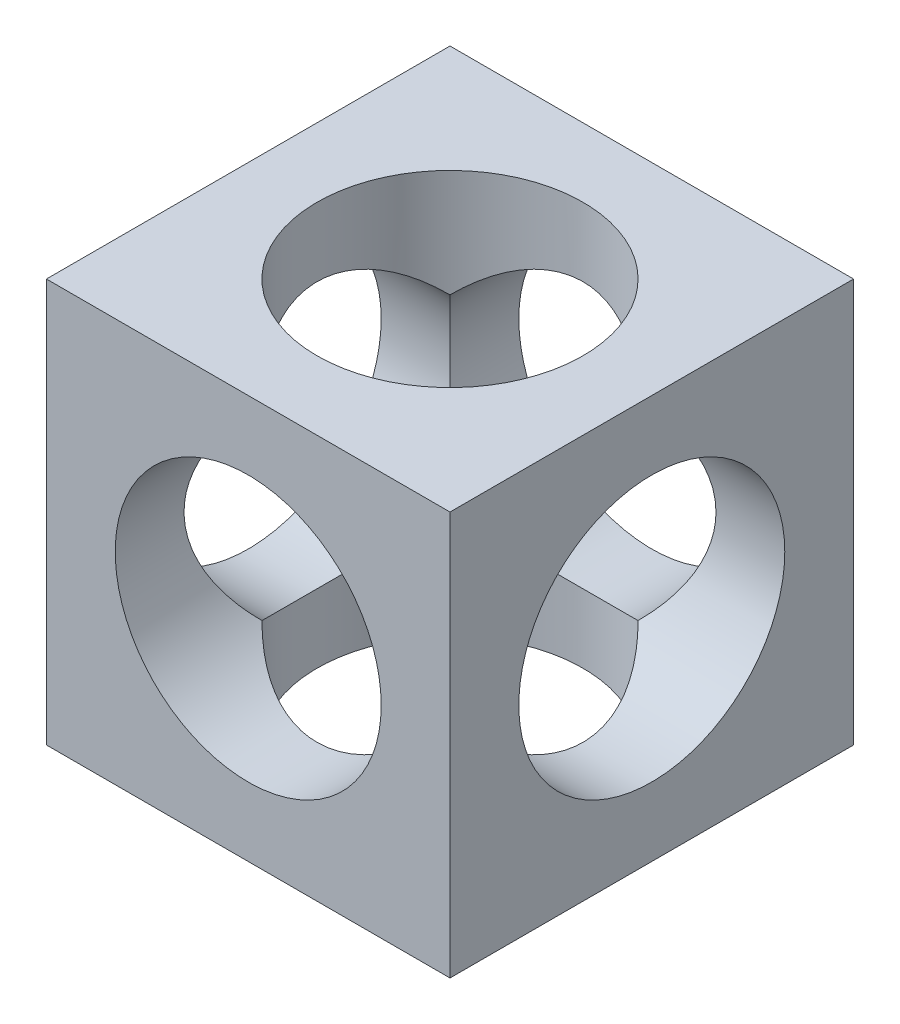
SolidWorks part; units mm, degrees
ref_plane "Front Plane" through (0, 0, 0) normal (0, 0, 1) x (1, 0, 0)
ref_plane "Top Plane" through (0, 0, 0) normal (0, 1, 0) x (1, 0, 0)
ref_plane "Right Plane" through (0, 0, 0) normal (1, 0, 0) x (0, 0, -1)
sketch "Esquisse1" plane through (0, 0, 0) normal (0, 0, 1) x (1, 0, 0)
  line L1 (-11, -11) -> (11, -11)
  line L2 (-11, -11) -> (-11, 11)
  line L3 (-11, 11) -> (11, 11)
  line L4 (11, -11) -> (11, 11)
  line L5 (-11, -11) -> (11, 11) construction
  line L6 (-11, 11) -> (11, -11) construction
  point P0 (0, 0)
  dimension "D1" = 22
extrude "Boss.-Extru.1" add sketch "Esquisse1" along normal blind 22
hole_wizard "Dégagement M131" positions "Esquisse3D1" profile "Esquisse2" hole size "M13" standard "ISO"
sketch3d "Esquisse3D1"
  line L0 (0, 11, 22) -> (0, 11, 0) construction
  line L1 (11, 11, 22) -> (-11, 11, 22) construction
  line L2 (11, 11, 0) -> (-11, 11, 0) construction
  line L4 (-11, 11, 11) -> (11, 11, 11) construction
  line L5 (-11, 11, 22) -> (-11, 11, 0) construction
  line L6 (11, 11, 22) -> (11, 11, 0) construction
  line L10 (11, 11, 11) -> (11, -11, 11) construction
  line L11 (11, -11, 22) -> (11, -11, 0) construction
  line L13 (0, 11, 22) -> (0, -11, 22) construction
  line L14 (-11, -11, 22) -> (11, -11, 22) construction
  point P0 (0, 11, 11)
  point P2 (0, 0, 22)
  point P4 (11, 0, 11)
sketch "Esquisse2" plane through (0, 11, 11) normal (1, 0, 0) x (0, 0, 1)
  line L0 (0, 0) -> (0, 3.75)
  line L1 (0, 3.75) -> (7.25, 3.75)
  line L2 (7.25, 3.75) -> (7.25, 0)
  line L5 (7.25, 0) -> (0, 0)
  line L11 (0, -6.35) -> (0, 107.95) construction
  dimension "Diamètre du perçage jusqu'au prochain" = 14.5
  dimension "Profondeur du perçage jusqu'au prochain" = 3.75
